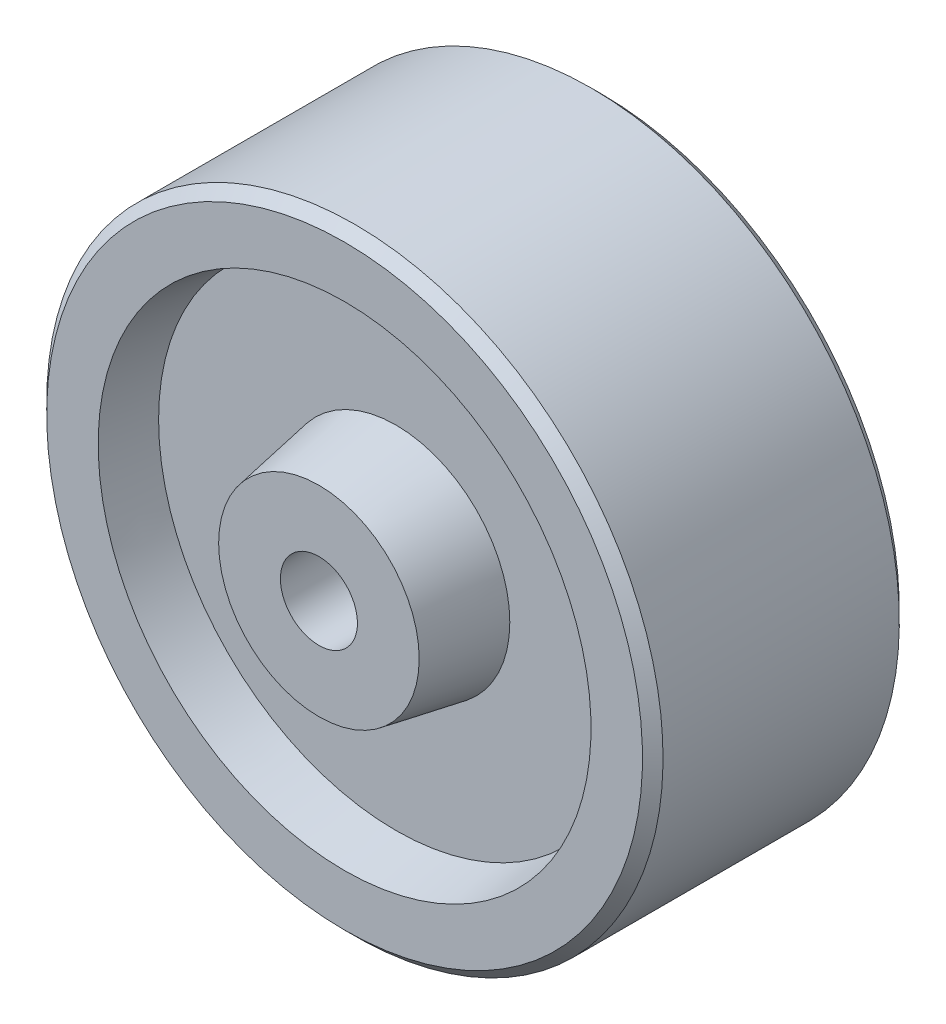
SolidWorks part; units mm, degrees
ref_plane "Front" through (0, 0, 0) normal (0, 0, 1) x (1, 0, 0)
ref_plane "Top" through (0, 0, 0) normal (0, 1, 0) x (1, 0, 0)
ref_plane "Right" through (0, 0, 0) normal (1, 0, 0) x (0, 0, -1)
sketch "Layout " plane through (0, 0, 0) normal (1, 0, 0) x (0, 0, -1)
  line L0 (0, 38.1) -> (0, -38.1) construction
  line L1 (-15.875, 38.1) -> (15.875, 38.1) construction
  line L2 (-19.05, 0) -> (19.05, 0) construction
  line L3 (0, 4.7625) -> (-19.05, 4.7625) construction
  dimension "Diameter" = 76.2
  dimension "Hub Length" = 38.1
  dimension "Width" = 31.75
  dimension "For Axle" = 9.525
sketch "Sketch2" plane through (0, 0, 0) normal (1, 0, 0) x (0, 0, -1)
  line L0 (0, 38.1) -> (-15.875, 38.1)
  line L1 (-15.875, 38.1) -> (-15.875, 30.4654)
  line L2 (-15.875, 30.4654) -> (-9.525, 29.3457)
  line L3 (-9.525, 29.3457) -> (-9.525, 21.7112)
  line L4 (-9.525, 14.0766) -> (-19.05, 12.3971)
  line L5 (-19.05, 12.3971) -> (-19.05, 4.7625)
  line L6 (-19.05, 4.7625) -> (0, 4.7625)
  line L7 (0, 38.1) -> (0, -38.1) construction
  line L8 (0, 38.1) -> (0, 4.7625)
  line L9 (-19.05, 0) -> (19.05, 0) construction
  line L10 (-19.05, 0) -> (19.05, 0) construction
  line L11 (0, 4.7625) -> (-19.05, 4.7625) construction
  line L12 (-9.525, 21.7112) -> (-9.525, 14.0766)
  dimension "D1" = 100
  dimension "D2" = 100
  dimension "D3" = 6.35
revolve "Revolve1" add sketch "Sketch2" angle 360 about L10
chamfer "Chamfer1" distance 1.27 angle 45 1 edges at (0, -38.1, 15.875)
mirror "Mirror2" about plane through (0, 0, 0) normal (0, 0, 1) of bodies 109
equation "\"D2@Sketch2\"=\"D1@Sketch2\""
